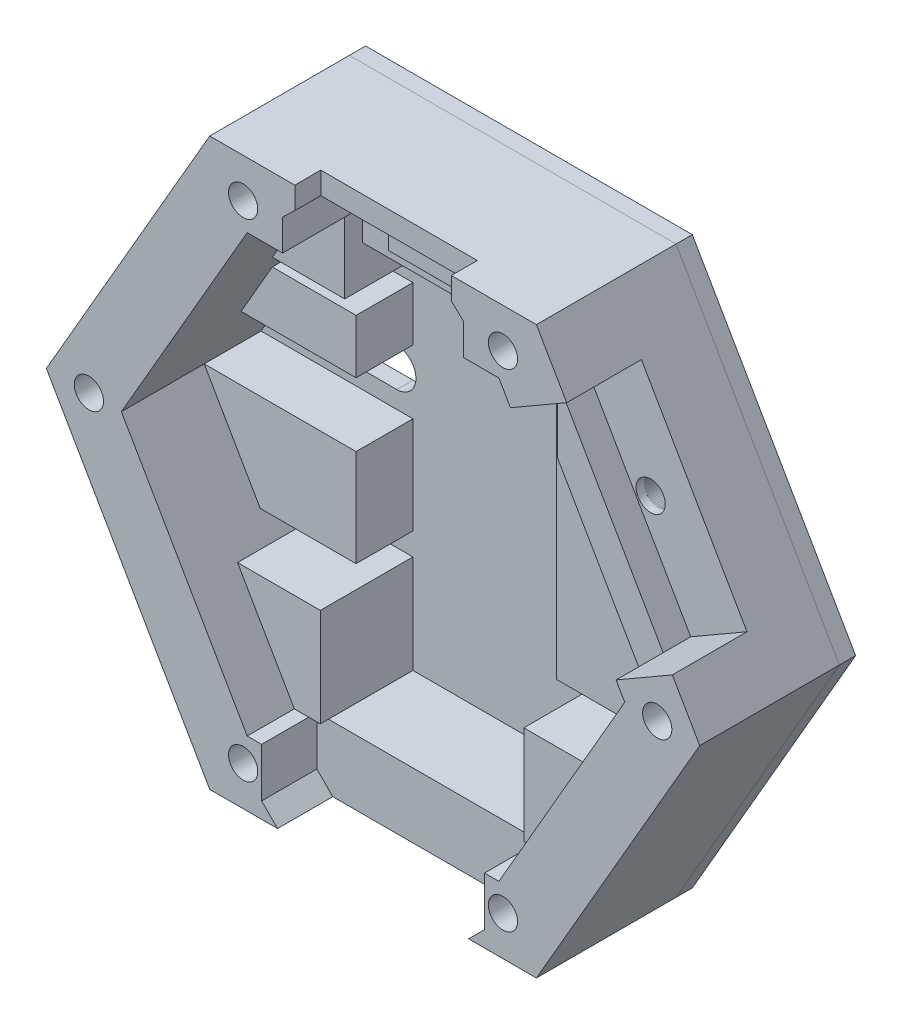
SolidWorks part; units mm, degrees
ref_plane "前视基准面" through (0, 0, 0) normal (0, 0, 1) x (1, 0, 0)
ref_plane "上视基准面" through (0, 0, 0) normal (0, 1, 0) x (1, 0, 0)
ref_plane "右视基准面" through (0, 0, 0) normal (1, 0, 0) x (0, 0, -1)
sketch "草图1" plane through (0, 0, 0) normal (0, 0, 1) x (1, 0, 0)
  line L0 (10.0594, 17.4234) -> (-10.0594, 17.4234)
  line L1 (15.5, 0) -> (7.75, 13.4234)
  line L2 (7.75, 13.4234) -> (-7.75, 13.4234)
  line L3 (-7.75, 13.4234) -> (-15.5, 0)
  line L4 (-15.5, 0) -> (-7.75, -13.4234)
  line L5 (-7.75, -13.4234) -> (7.75, -13.4234)
  line L6 (7.75, -13.4234) -> (15.5, 0)
  line L7 (-10.0594, 17.4234) -> (-20.1188, 0)
  line L8 (-20.1188, 0) -> (-10.0594, -17.4234)
  line L9 (-10.0594, -17.4234) -> (10.0594, -17.4234)
  line L10 (10.0594, -17.4234) -> (20.1188, 0)
  line L11 (20.1188, 0) -> (10.0594, 17.4234)
  circle A0 centre (0, 0) radius 13.4234 construction
  dimension "D1" = 15.5
  dimension "D2" = 4
extrude "凸台-拉伸1" add sketch "草图1" along normal blind 7
sketch "草图2" plane through (0, 0, 7) normal (0, 0, 1) x (1, 0, 0)
  line L0 (-5.5735, 13.4234) -> (-5.5735, 15.3499)
  line L1 (7.75, 13.4234) -> (-7.75, 13.4234) construction
  line L2 (-5.5735, 15.3499) -> (-4.8201, 16.0618)
  line L3 (5.5735, 13.4234) -> (5.5735, 15.3499)
  line L4 (0, 19.3164) -> (0, 10.8862) construction
  line L5 (5.5735, 15.3499) -> (4.8201, 16.0618)
  line L6 (-4.8201, 16.0618) -> (4.8201, 16.0618)
  line L7 (5.5735, 13.4234) -> (-5.5735, 13.4234)
  line L8 (0, -18.1349) -> (0, -9.4848) construction
  line L9 (6.8633, -13.4234) -> (6.8633, -16.4408)
  line L10 (-7.75, -13.4234) -> (7.75, -13.4234) construction
  line L11 (6.8633, -16.4408) -> (5.8807, -17.4234)
  line L12 (-10.0594, -17.4234) -> (10.0594, -17.4234) construction
  line L13 (-6.8633, -16.4408) -> (-5.8807, -17.4234)
  line L14 (-6.8633, -13.4234) -> (-6.8633, -16.4408)
  line L15 (-5.8807, -17.4234) -> (5.8807, -17.4234)
  line L16 (-6.8633, -13.4234) -> (6.8633, -13.4234)
  line M8 (-10.0594, -17.4234) -> (10.0594, -17.4234)
  line M12 (7.75, -13.4234) -> (-7.75, -13.4234)
extrude "切除-拉伸1" cut sketch "草图2" against normal blind 1.8 contours L14 L13 L11 L9 M12 M8 | L6 L5 L3 L7 L0 L2
sketch "草图3" plane through (0, 0, 7) normal (0, 0, 1) x (1, 0, 0)
  line L0 (8.4606, 12.1926) -> (11.9247, 14.1926)
  line L1 (15.5, 0) -> (7.75, 13.4234) construction
  line L2 (20.1188, 0) -> (10.0594, 17.4234) construction
  line L3 (11.9247, 14.1926) -> (18.4288, 2.9271)
  line L4 (18.4288, 2.9271) -> (14.9647, 0.9271)
  line L5 (14.9647, 0.9271) -> (8.4606, 12.1926)
extrude "切除-拉伸2" cut sketch "草图3" against normal blind 3
sketch "草图4" plane through (0, 0, 0) normal (0, 0, -1) x (-1, 0, 0)
  line L0 (-11.2456, -7.3688) -> (-6.3823, -7.3688)
  line L1 (-7.75, -13.4234) -> (-15.5, 0) construction
  line L2 (-6.3823, -7.3688) -> (-6.3823, -13.4234)
  line L3 (7.75, -13.4234) -> (-7.75, -13.4234) construction
  line L4 (-6.3823, -13.4234) -> (-7.75, -13.4234)
  line L5 (-7.75, -13.4234) -> (-11.2456, -7.3688)
  line L6 (6.1453, -7.3688) -> (11.2456, -7.3688)
  line L7 (15.5, 0) -> (7.75, -13.4234) construction
  line L8 (11.2456, -7.3688) -> (7.75, -13.4234)
  line L9 (7.75, -13.4234) -> (6.1453, -13.4234)
  line L10 (6.1453, -13.4234) -> (6.1453, -7.3688)
  line L11 (6.1453, 13.4234) -> (6.1453, 8.4885)
  line L12 (-7.75, 13.4234) -> (7.75, 13.4234) construction
  line L13 (6.1453, 8.4885) -> (10.5991, 8.4885)
  line L14 (7.75, 13.4234) -> (15.5, 0) construction
  line L15 (10.5991, 8.4885) -> (7.75, 13.4234)
  line L16 (7.75, 13.4234) -> (6.1453, 13.4234)
  line L17 (-8.4606, 12.1926) -> (-6.6742, 11.1612)
  line L19 (-6.6742, 11.1612) -> (-13.5028, -0.6663)
  line L20 (-13.5028, -0.6663) -> (-15.2892, 0.3651)
  line L21 (-15.5, 0) -> (-7.75, 13.4234) construction
  line L22 (-15.2892, 0.3651) -> (-8.4606, 12.1926)
extrude "凸台-拉伸4" add sketch "草图4" against normal blind 5.7 separate body
sketch "草图6" plane through (0, 0, 0) normal (0, 0, -1) x (-1, 0, 0)
  line L0 (-7.1671, 10.3074) -> (-6.1899, 10.3074)
  line L1 (-13.5028, -0.6663) -> (-6.6742, 11.1612) construction
  line L2 (-6.1899, 10.3074) -> (-6.1899, -5.9802)
  line L3 (-6.1899, -5.9802) -> (-12.0474, -5.9802)
  line L4 (-7.75, -13.4234) -> (-15.5, 0) construction
  line L7 (-15.5, 0) -> (-7.75, 13.4234) construction
  line L8 (-9.549, 10.3074) -> (-7.1671, 10.3074)
  line L9 (-5.839, 13.4234) -> (-5.839, 11.3427)
  line L10 (-7.75, 13.4234) -> (7.75, 13.4234) construction
  line L11 (-5.839, 11.3427) -> (5.7465, 11.3427)
  line L12 (5.7465, 11.3427) -> (5.7465, 13.4234)
  line L14 (6.1453, 7.2648) -> (6.1453, 3.9358)
  line L15 (6.1453, -5.9802) -> (12.0474, -5.9802)
  line L16 (15.5, 0) -> (7.75, -13.4234) construction
  line L20 (5.7465, 13.4234) -> (5.7465, 15.341)
  line L21 (5.7465, 15.341) -> (-5.839, 15.341)
  line L22 (-5.839, 15.341) -> (-5.839, 13.4234)
  line L23 (-9.549, 10.3074) -> (-11.4726, 10.3074)
  line L24 (-11.4726, 10.3074) -> (-17.3636, 0)
  line L25 (-17.3636, 0) -> (-13.6263, -5.9802)
  line L26 (-13.6263, -5.9802) -> (-12.0474, -5.9802)
  line L28 (12.8121, 7.2648) -> (14.8926, 3.9358)
  line L29 (17.3523, 0) -> (13.9344, -5.9802)
  line L30 (13.9344, -5.9802) -> (12.0474, -5.9802)
  line L31 (6.1453, 7.2648) -> (12.8121, 7.2648)
  line L32 (6.1453, 3.9358) -> (14.8926, 3.9358)
  line L33 (17.3523, 0) -> (6.1453, 0)
  line L34 (6.1453, 0) -> (6.1453, -5.9802)
extrude "凸台-拉伸21" add sketch "草图6" against normal blind 3.5 separate body
sketch "草图12" plane through (0, 0, 0) normal (0, 0, -1) x (-1, 0, 0)
  line L1 (-10.0594, 17.4234) -> (-20.1188, 0)
  line L2 (-20.1188, 0) -> (-10.0594, -17.4234)
  line L3 (-10.0594, -17.4234) -> (10.0594, -17.4234)
  line L4 (10.0594, -17.4234) -> (20.1188, 0)
  line L5 (20.1188, 0) -> (10.0594, 17.4234)
  line L6 (10.0594, 17.4234) -> (-10.0594, 17.4234)
  circle A0 centre (0, 0) radius 17.4234 construction
extrude "凸台-拉伸22" add sketch "草图12" along normal blind 1 separate body
sketch "草图13" plane through (0, 0, -1) normal (0, 0, -1) x (-1, 0, 0)
  line L0 (10.1234, 2.2395) -> (7.1359, 2.2395) construction
  line L1 (10.1234, 1.0625) -> (7.1359, 1.0625)
  line L2 (10.1234, 3.4166) -> (7.1359, 3.4166)
  line L3 (8.6297, 1.7395) -> (8.6297, 2.7395) construction
  arc A0 (10.1234, 1.0625) -> (10.1234, 3.4166) centre (10.1234, 2.2395) ccw
  arc A1 (7.1359, 3.4166) -> (7.1359, 1.0625) centre (7.1359, 2.2395) ccw
  point P2 (8.6297, 2.2395)
extrude "切除-拉伸3" cut sketch "草图13" against normal blind 10
sketch "草图14" plane through (0, 0, 5.7) normal (0, 0, 1) x (1, 0, 0)
  line L0 (-7.75, 13.4234) -> (-6.1453, 13.4234)
  line L1 (-6.1453, 13.4234) -> (-6.1453, 8.4635)
  line L2 (8.4603, 12.1924) -> (8.4603, 8.0675)
  line L3 (-7.75, 13.4234) -> (-10.5991, 8.4885)
  line L4 (-10.5991, 8.4885) -> (-6.1453, 8.4635)
  line L5 (6.6742, 11.1612) -> (8.4606, 12.1926) construction
  line L6 (13.5028, -0.6663) -> (6.6742, 11.1612) construction
  line L7 (8.4603, 8.0675) -> (6.6742, 11.1612)
  line L8 (6.6742, 11.1612) -> (8.4603, 12.1924)
extrude "切除-拉伸4" cut sketch "草图14" against normal blind 1.5
sketch "草图15" plane through (0, 0, 5.2) normal (0, 0, 1) x (1, 0, 0)
  line L0 (0, 17.0326) -> (0, 11.8468) construction
  line L1 (-2.4446, 16.0618) -> (-2.4446, 13.4234)
  line L2 (-4.8201, 16.0618) -> (4.8201, 16.0618) construction
  line L3 (5.5735, 13.4234) -> (-5.5735, 13.4234) construction
  line L4 (-2.4446, 13.4234) -> (-5.5735, 13.4234)
  line L5 (-5.5735, 13.4234) -> (-5.5735, 15.3499)
  line L6 (-5.5735, 15.3499) -> (-4.8201, 16.0618) construction
  line L7 (-5.5735, 15.3499) -> (-4.8201, 16.0618) construction
  line L8 (-5.5735, 15.3499) -> (-4.8201, 16.0618)
  line L9 (-4.8201, 16.0618) -> (-2.4446, 16.0618)
  line L10 (4.8201, 16.0618) -> (2.4446, 16.0618)
  line L11 (5.5735, 15.3499) -> (4.8201, 16.0618)
  line L12 (5.5735, 13.4234) -> (5.5735, 15.3499)
  line L13 (2.4446, 13.4234) -> (5.5735, 13.4234)
  line L14 (2.4446, 16.0618) -> (2.4446, 13.4234)
extrude "切除-拉伸5" cut sketch "草图15" against normal blind 1
sketch "草图16" plane through (0, 0, 7) normal (0, 0, 1) x (1, 0, 0)
  line L0 (7.75, 17.4234) -> (17.8094, 0)
  line L1 (10.0594, 17.4234) -> (-10.0594, 17.4234) construction
  line L2 (10.0594, -17.4234) -> (20.1188, 0) construction
  line L3 (20.1188, 0) -> (18.4288, 2.9271) construction
  line L4 (11.9247, 14.1926) -> (10.0594, 17.4234) construction
  line L5 (7.75, 17.4234) -> (10.0594, 17.4234)
  line L6 (10.0594, 17.4234) -> (20.1188, 0)
  line L7 (20.1188, 0) -> (18.9641, -2)
  line L8 (17.8094, 0) -> (7.75, -17.4234)
  line L9 (10.0594, -17.4234) -> (7.75, -17.4234)
  line L11 (18.9641, -2) -> (10.0594, -17.4234)
  line L12 (0, 18.7265) -> (0, -21.8829) construction
  line L13 (-18.9641, -2) -> (-10.0594, -17.4234)
  line L14 (-10.0594, -17.4234) -> (-7.75, -17.4234)
  line L15 (-17.8094, 0) -> (-7.75, -17.4234)
  line L16 (-20.1188, 0) -> (-18.9641, -2)
  line L17 (-10.0594, 17.4234) -> (-20.1188, 0)
  line L18 (-7.75, 17.4234) -> (-10.0594, 17.4234)
  line L19 (-7.75, 17.4234) -> (-17.8094, 0)
  dimension "D1" = 2
  dimension "D2" = 2
sketch "草图18" plane through (0, 0, 7) normal (0, 0, 1) x (1, 0, 0)
  line L0 (-4.8201, 16.0618) -> (-4.8201, 17.4234)
  line L1 (4.8201, 16.0618) -> (4.8201, 17.4234)
  line L2 (-4.8201, 17.4234) -> (-10.0594, 17.4234)
  line L9 (18.4288, 2.9271) -> (14.9647, 0.9271)
  line L10 (14.9647, 0.9271) -> (15.5, 0)
  line L11 (15.5, 0) -> (7.75, -13.4234)
  line L12 (7.75, -13.4234) -> (6.8633, -13.4234)
  line L13 (6.8633, -13.4234) -> (6.8633, -16.4408)
  line L14 (6.8633, -16.4408) -> (5.8807, -17.4234)
  line L15 (5.8807, -17.4234) -> (10.0594, -17.4234)
  line L16 (10.0594, -17.4234) -> (20.1188, 0)
  line L17 (20.1188, 0) -> (18.4288, 2.9271)
  line L18 (18.4288, 2.9271) -> (14.9647, 0.9271)
  line L19 (8.4606, 12.1926) -> (11.9247, 14.1926)
  line L20 (11.9247, 14.1926) -> (10.0594, 17.4234)
  line L21 (10.0594, 17.4234) -> (-10.0594, 17.4234)
  line L22 (-10.0594, 17.4234) -> (-20.1188, 0)
  line L23 (-20.1188, 0) -> (-10.0594, -17.4234)
  line L24 (-10.0594, -17.4234) -> (-5.8807, -17.4234)
  line L25 (-5.8807, -17.4234) -> (-6.8633, -16.4408)
  line L26 (-6.8633, -16.4408) -> (-6.8633, -13.4234)
  line L27 (-6.8633, -13.4234) -> (-7.75, -13.4234)
  line L28 (-7.75, -13.4234) -> (-15.5, 0)
  line L29 (-15.5, 0) -> (-7.75, 13.4234)
  line L30 (-7.75, 13.4234) -> (-5.5735, 13.4234)
  line L31 (-5.5735, 13.4234) -> (-5.5735, 15.3499)
  line L32 (-5.5735, 15.3499) -> (-4.8201, 16.0618)
  line L33 (-4.8201, 16.0618) -> (4.8201, 16.0618)
  line L34 (4.8201, 16.0618) -> (5.5735, 15.3499)
  line L35 (5.5735, 15.3499) -> (5.5735, 13.4234)
  line L36 (5.5735, 13.4234) -> (7.75, 13.4234)
  line L37 (7.75, 13.4234) -> (8.4606, 12.1926)
  line L38 (8.4606, 12.1926) -> (11.9247, 14.1926)
  line L39 (11.9247, 14.1926) -> (10.0594, 17.4234)
  line L40 (10.0594, 17.4234) -> (4.8201, 17.4234)
  line L41 (-10.0594, 17.4234) -> (-20.1188, 0)
  line L42 (-20.1188, 0) -> (-10.0594, -17.4234)
  line L43 (-10.0594, -17.4234) -> (-5.8807, -17.4234)
  line L44 (-5.8807, -17.4234) -> (-6.8633, -16.4408)
  line L45 (-6.8633, -16.4408) -> (-6.8633, -13.4234)
  line L46 (-6.8633, -13.4234) -> (-7.75, -13.4234)
  line L47 (-7.75, -13.4234) -> (-15.5, 0)
  line L48 (-15.5, 0) -> (-7.75, 13.4234)
  line L49 (-7.75, 13.4234) -> (-5.5735, 13.4234)
  line L50 (-5.5735, 13.4234) -> (-5.5735, 15.3499)
  line L51 (-5.5735, 15.3499) -> (-4.8201, 16.0618)
  line L53 (4.8201, 16.0618) -> (5.5735, 15.3499)
  line L54 (5.5735, 15.3499) -> (5.5735, 13.4234)
  line L55 (5.5735, 13.4234) -> (7.75, 13.4234)
  line L56 (7.75, 13.4234) -> (8.4606, 12.1926)
  line L57 (14.9647, 0.9271) -> (15.5, 0)
  line L58 (15.5, 0) -> (7.75, -13.4234)
  line L59 (7.75, -13.4234) -> (6.8633, -13.4234)
  line L60 (6.8633, -13.4234) -> (6.8633, -16.4408)
  line L61 (6.8633, -16.4408) -> (5.8807, -17.4234)
  line L62 (5.8807, -17.4234) -> (10.0594, -17.4234)
  line L63 (10.0594, -17.4234) -> (20.1188, 0)
  line L64 (20.1188, 0) -> (18.4288, 2.9271)
  dimension "D1" = 0
  dimension "D2" = 0
extrude "凸台-拉伸23" add sketch "草图18" along normal blind 1.6
sketch "草图17" plane through (0, 0, -1) normal (0, 0, -1) x (-1, 0, 0)
  line L0 (-25.1496, 0) -> (29.1565, 0) construction
  line L1 (0, -23.8718) -> (0, 23.2815) construction
  circle A0 centre (8, 15) radius 0.9
  circle A1 centre (8, -15) radius 0.9
  circle A2 centre (-8, -15) radius 0.9
  circle A3 centre (-8, 15) radius 0.9
  circle A4 centre (17.5, 0) radius 0.9
  circle A5 centre (-17.5, 0) radius 0.9
  dimension "D3" = 1.8
  dimension "D4" = 17.5
  dimension "D5" = 1.8
  dimension "D1" = 15
  dimension "D2" = 8
extrude "切除-拉伸6" cut sketch "草图17" against normal blind 20
sketch "草图19" plane through (0, 0, -1) normal (0, 0, -1) x (-1, 0, 0)
  line L0 (0, 22.8566) -> (0, -20.1355) construction
  line L1 (0, 18.7265) -> (0, -21.8829) construction
  circle A0 centre (-8, 15) radius 1.75
  circle A1 centre (-17.5, 0) radius 1.75
  circle A2 centre (-8, -15) radius 1.75
  circle A3 centre (8, -15) radius 1.75
  circle A4 centre (17.5, 0) radius 1.75
  circle A5 centre (8, 15) radius 1.75
  dimension "D1" = 3.5
extrude "切除-拉伸7" cut sketch "草图19" against normal blind 2
sketch "草图20" plane through (0, 0, -1) normal (0, 0, -1) x (-1, 0, 0)
  line L0 (-8, 15) -> (15.7821, 15) construction
  line L1 (0, 18.7265) -> (0, -21.8829) construction
  line L2 (-23.712, 0) -> (29.0686, 0) construction
  line L3 (-15.0891, 8.7117) -> (-7.0284, 4.0578) construction
  line L4 (-10.0594, 17.4234) -> (-20.1188, 0) construction
  line L5 (-8, 15) -> (-13.9005, 4.7801) construction
  line L6 (0, 10.1479) -> (0, 4.0578) construction
  circle A0 centre (0, 15) radius 0.9
  circle A1 centre (-12.4952, 7.2141) radius 0.9
  circle A2 centre (12.4952, 7.2141) radius 0.9
  circle A3 centre (-12.4952, -7.2141) radius 0.9
  circle A4 centre (12.4952, -7.2141) radius 0.9
  circle A5 centre (0, -15) radius 0.9
extrude "切除-拉伸8" cut sketch "草图20" against normal blind 6 contours A0 | A1 | A2 | A4 | A3 | A5
